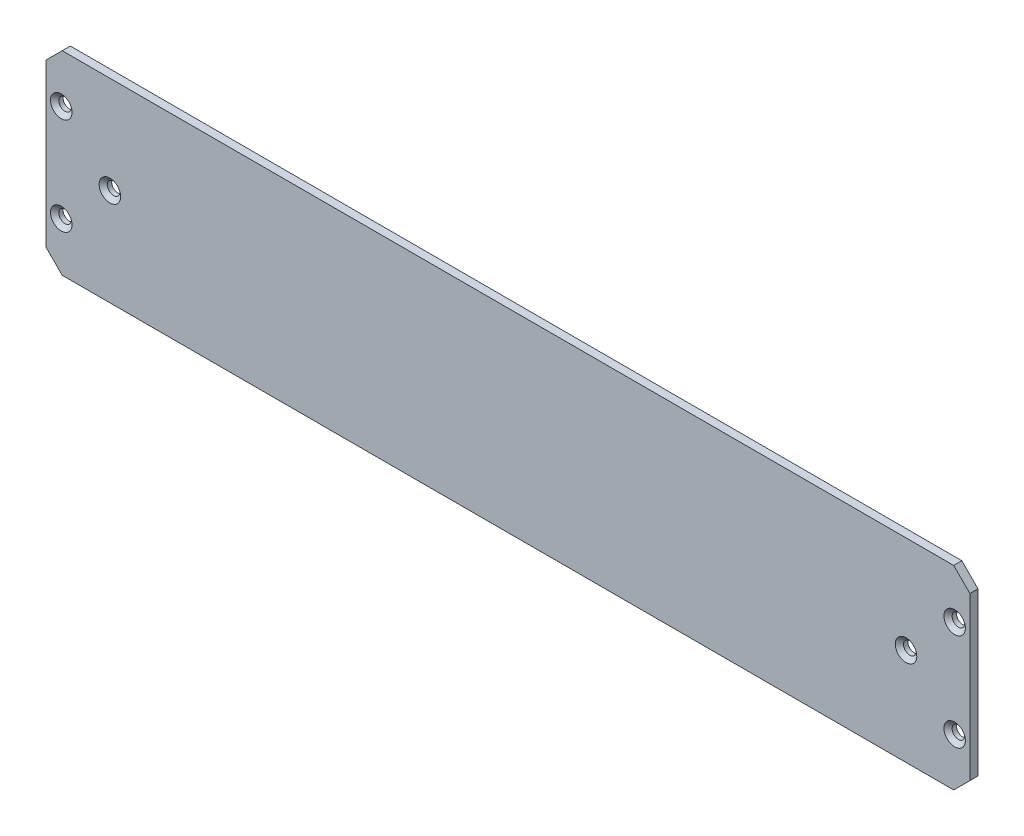
SolidWorks part; units mm, degrees
material "6061-T6 (SS)"
ref_plane "Front Plane" through (0, 0, 0) normal (0, 0, 1) x (1, 0, 0)
ref_plane "Top Plane" through (0, 0, 0) normal (0, 1, 0) x (1, 0, 0)
ref_plane "Right Plane" through (0, 0, 0) normal (1, 0, 0) x (0, 0, -1)
sketch "Sketch1" plane through (0, 0, 0) normal (0, 0, 1) x (1, 0, 0)
  line L5 (180.975, 38.1) -> (-180.975, 38.1)
  line L6 (180.975, 38.1) -> (180.975, -38.1)
  line L7 (180.975, -38.1) -> (-180.975, -38.1)
  line L8 (-180.975, 38.1) -> (-180.975, -38.1)
  line L9 (180.975, 38.1) -> (-180.975, -38.1) construction
  line L10 (180.975, -38.1) -> (-180.975, 38.1) construction
  point P0 (0, 0)
  point P5 (0, 0)
  dimension "D1" = 76.2
  dimension "D2" = 361.95
extrude "Boss-Extrude1" add sketch "Sketch1" along normal blind 3.175
hole_wizard "CSK for #8 Flat Head Machine Screw (100)1" positions "Sketch2" profile "Sketch3" countersink size "#8" standard "ANSI Inch" end condition through all
sketch "Sketch2" plane through (0, 0, 3.175) normal (0, 0, 1) x (1, 0, 0)
  line L8 (175, 43.9199) -> (175, -43.9199) construction
  line L9 (165.475, 43.9199) -> (184.525, 43.9199) construction
  line L10 (165.475, -43.9199) -> (184.525, -43.9199) construction
  line L12 (155.95, 43.9199) -> (155.95, -43.9199) construction
  line L13 (146.425, 43.9199) -> (165.475, 43.9199) construction
  line L14 (165.475, -43.9199) -> (146.425, -43.9199) construction
  line L15 (0, 0) -> (175, 0) construction
  line L17 (0, 0) -> (0, 38.1) construction
  line L18 (180.975, 38.1) -> (-180.975, 38.1) construction
  point P32 (175, 19.05)
  point P34 (175, -19.05)
  point P36 (155.95, 0)
  point P52 (0, 0)
  point P53 (-155.95, 0)
  point P54 (-175, -19.05)
  point P55 (-175, 19.05)
  dimension "D1" = 38.1
  dimension "D2" = 19.05
sketch "Sketch3" plane through (-175, 19.05, 3.175) normal (1, 0, 0) x (0, -1, 0)
  line L0 (0, 0) -> (0, 3.175)
  line L1 (0, 3.175) -> (2.4574, 3.175)
  line L2 (2.4574, 3.175) -> (2.4574, 1.4759)
  line L3 (2.4574, 1.4759) -> (4.2164, 0)
  line L5 (4.2164, 0) -> (0, 0)
  line L6 (-2.4574, 1.4759) -> (-4.2164, 0) construction
  line L11 (0, -6.35) -> (0, 107.95) construction
  dimension "Thru Hole Dia." = 4.9149
  dimension "Thru Hole Depth" = 3.175
  dimension "Near C'Sink Dia." = 8.4328
  dimension "Near C'Sink Angle" = 100
chamfer "Chamfer1" distance 6.35 angle 45 4 edges at (-180.975, 38.1, 1.5875) (-180.975, -38.1, 1.5875) (180.975, 38.1, 1.5875) (180.975, -38.1, 1.5875)
equation "\"D2@Sketch2\"=\"D1@Sketch2\"/2"
